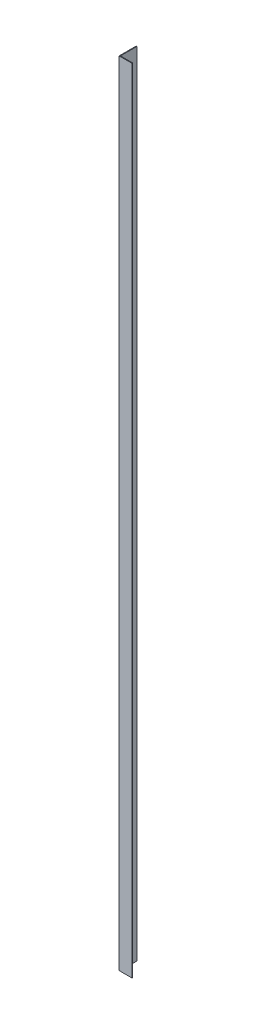
SolidWorks part; units mm, degrees
ref_plane "Front Plane" through (0, 0, 0) normal (0, 0, 1) x (1, 0, 0)
ref_plane "Top Plane" through (0, 0, 0) normal (0, 1, 0) x (1, 0, 0)
ref_plane "Right Plane" through (0, 0, 0) normal (1, 0, 0) x (0, 0, -1)
other "Configuration Table"
sketch "Sketch1" plane through (0, 0, 0) normal (0, 1, 0) x (1, 0, 0)
  line L0 (700, -40) -> (700, -38.5)
  line L1 (700, -38.5) -> (671.5, -38.5)
  line L2 (671.5, -38.5) -> (671.5, 0)
  line L3 (671.5, 0) -> (670, 0)
  line L4 (670, 0) -> (670, -40)
  line L5 (670, -40) -> (700, -40)
extrude "OVEN_sove_sag_1" add sketch "Sketch1" along normal blind 1850 from offset 120 separate body
